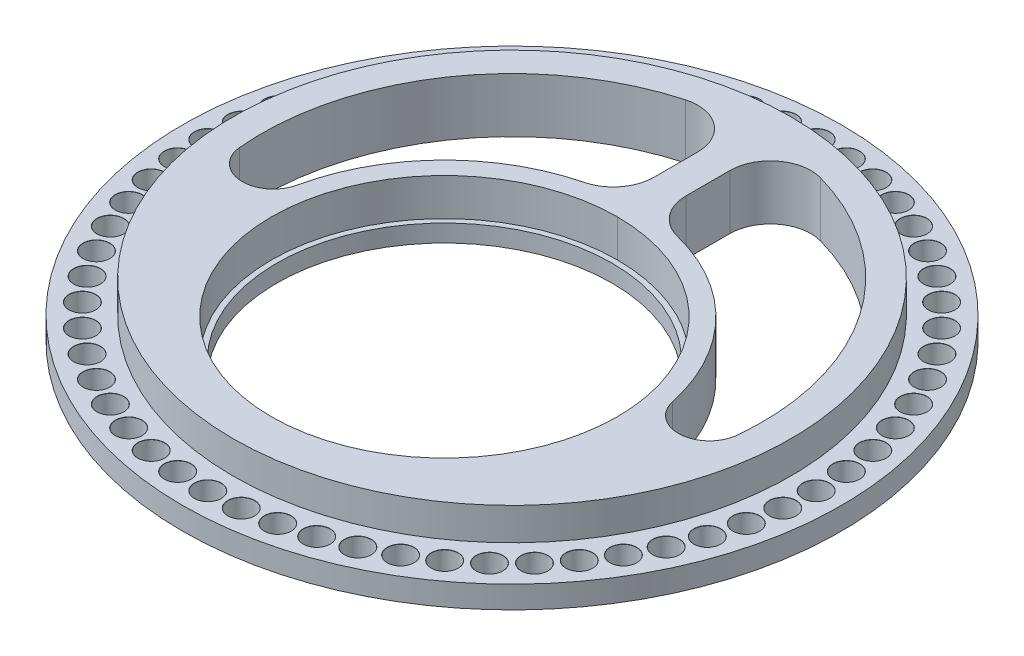
SolidWorks part; units mm, degrees
material "6061-T6 (SS)"
ref_plane "X-Y Datum" through (0, 0, 0) normal (0, 0, 1) x (1, 0, 0)
ref_plane "X-Z Datum" through (0, 0, 0) normal (0, 1, 0) x (1, 0, 0)
ref_plane "Y-Z Datum" through (0, 0, 0) normal (1, 0, 0) x (0, 0, -1)
sketch "Sketch1" plane through (0, 0, 0) normal (0, 1, 0) x (1, 0, 0)
  line L0 (0, 0) -> (0, -12.7) construction
  line L1 (0, -43.0151) -> (0, 43.0151) construction
  line L2 (0, 52.3875) -> (0, 61.9125) construction
  circle A0 centre (0, -12.7) radius 30.988
  circle A1 centre (0, 0) radius 52.3875 construction
  circle A2 centre (0, 0) radius 61.9125
  circle A3 centre (0, 0) radius 57.15 construction
  point P12 (0, 57.15)
  dimension "D2" = 61.976
  dimension "D3" = 104.775
  dimension "D4" = 123.825
  dimension "D5" = 114.3
  dimension "D1" = 12.7
extrude "Slotted-Body Extrude" add sketch "Sketch1" along normal blind 4.191
sketch "Sketch5" plane through (0, 4.191, 0) normal (0, 1, 0) x (1, 0, 0)
  circle A0 centre (0, 0) radius 52.3875 construction
  circle A1 centre (0, 0) radius 52.3875
extrude "Boss-Extrude3" add sketch "Sketch5" along normal blind 6.08
sketch "Sketch6" plane through (0, 0, 0) normal (0, -1, 0) x (1, 0, 0)
  line L4 (-3.014, -37.9067) -> (-3.014, -29.6741)
  line L6 (3.014, -37.9067) -> (3.014, -29.6741)
  circle A0 centre (0, 12.7) radius 30.988 construction
  circle A1 centre (0, 12.7) radius 30.988 construction
  circle A2 centre (0, 12.7) radius 32.512
  arc A9 (-35.2562, 5.0907) -> (-8.7792, -22.2832) centre (0, 12.7) ccw
  arc A10 (-46.783, 4.406) -> (-12.6921, -45.2435) centre (0, 0) ccw
  arc A11 (-46.783, 4.406) -> (-35.2562, 5.0907) centre (-40.9667, 3.8583) cw
  arc A12 (46.783, 4.406) -> (35.2562, 5.0907) centre (40.9667, 3.8583) ccw
  arc A15 (12.6921, -45.2435) -> (46.783, 4.406) centre (0, 0) ccw
  arc A16 (8.7792, -22.2832) -> (35.2562, 5.0907) centre (0, 12.7) ccw
  arc A17 (3.014, -29.6741) -> (8.7792, -22.2832) centre (10.634, -29.6741) cw
  arc A18 (3.014, -37.9067) -> (12.6921, -45.2435) centre (10.634, -37.9067) ccw
  arc A19 (-3.014, -29.6741) -> (-8.7792, -22.2832) centre (-10.634, -29.6741) ccw
  arc A20 (-3.014, -37.9067) -> (-12.6921, -45.2435) centre (-10.634, -37.9067) cw
  circle A21 centre (0, 0) radius 61.9125 construction
  point P23 (3.014, -23.2419)
  point P27 (3.014, -46.8932)
  point P30 (0, 0)
  point P31 (-3.014, -23.2419)
  point P32 (0, 0)
  point P36 (-3.014, -46.8932)
  dimension "D1" = 65.024
  dimension "D2" = 7.62
  dimension "D3" = 5.842
  dimension "D4" = 46.99
  dimension "D5" = 7.62
  dimension "D6" = 36.068
  dimension "D7" = 7.62
  dimension "D8" = 8.2326
extrude "Cut-Extrude5" cut sketch "Sketch6" against normal through all
sketch "Sketch8" plane through (0, 0, 0) normal (0, -1, 0) x (1, 0, 0)
  circle A0 centre (0, 12.7) radius 32.512 construction
  circle A1 centre (0, 12.7) radius 32.512
  circle A2 centre (0, 12.7) radius 31.496
  dimension "D1" = 62.992
extrude "Boss-Extrude4" add sketch "Sketch8" against normal blind 3.255 separate body
hole_wizard "Ø5.0mm Dowel Hole1" positions "Sketch9" profile "Sketch10" hole size "Ø5.0" standard "ANSI Metric" end condition through all
sketch "Sketch9" plane through (0, 4.191, 0) normal (0, 1, 0) x (1, 0, 0)
  point P0 (0, 57.15)
sketch "Sketch10" plane through (0, 4.191, -57.15) normal (1, 0, 0) x (0, 0, 1)
  line L0 (0, 0) -> (0, 4.191)
  line L1 (0, 4.191) -> (2.5, 4.191)
  line L2 (2.5, 4.191) -> (2.5, 0.025)
  line L3 (2.5, 0.025) -> (2.525, 0)
  line L5 (2.525, 0) -> (0, 0)
  line L6 (-2.5, 0.025) -> (-2.525, 0) construction
  line L11 (0, -6.35) -> (0, 107.95) construction
  dimension "Thru Hole Dia." = 5
  dimension "Thru Hole Depth" = 4.191
  dimension "Near C'Sink Dia." = 5.05
  dimension "Near C'Sink Angle" = 90
pattern_circular "CirPattern1" count 60 over 360 about axis through (0, 0, 0) along (0, 1, 0) of "Ø5.0mm Dowel Hole1"
ref_point "Point1"
ref_plane "Plane1" through (0, 0, 0) normal (1, 0, 0) x (0, 0, -1)
split line "Split Line1"
curve "CompCurve1"
